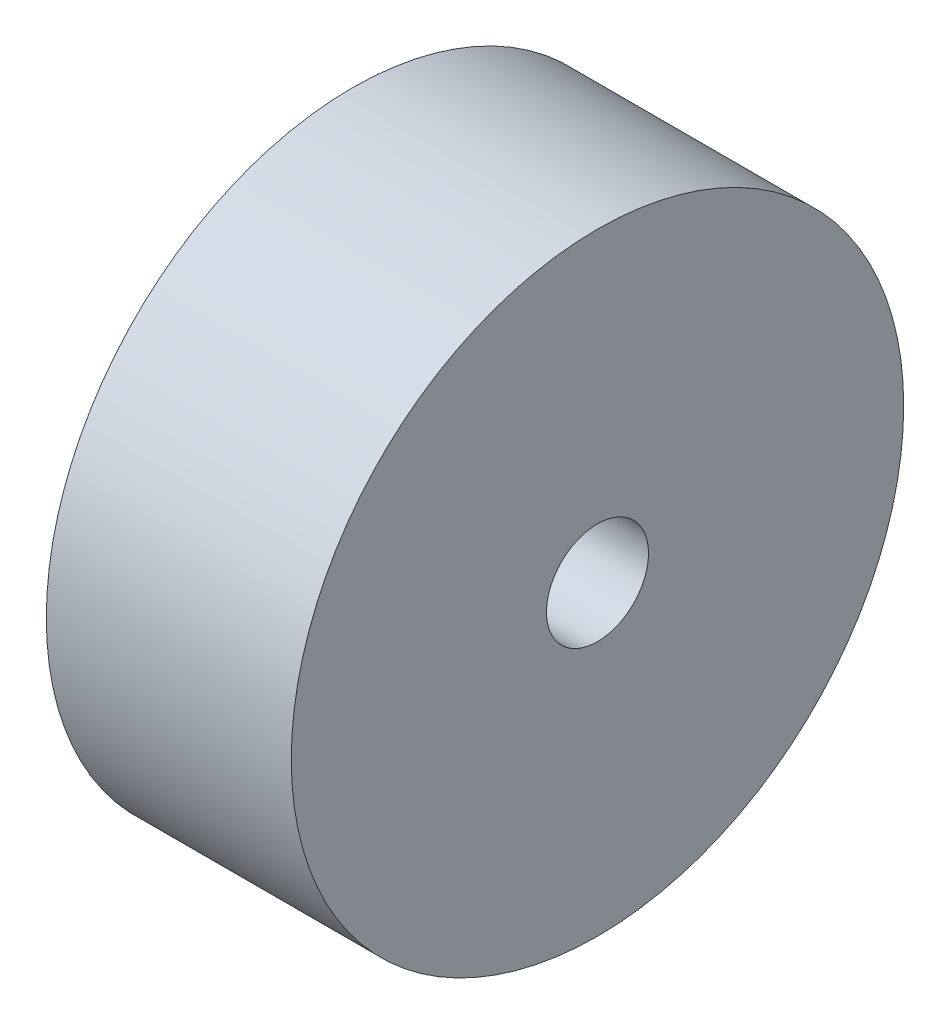
SolidWorks part; units mm, degrees
ref_plane "Front Plane" through (0, 0, 0) normal (0, 0, 1) x (1, 0, 0)
ref_plane "Top Plane" through (0, 0, 0) normal (0, 1, 0) x (1, 0, 0)
ref_plane "Right Plane" through (0, 0, 0) normal (1, 0, 0) x (0, 0, -1)
sketch "Sketch1" plane through (0, 0, 0) normal (1, 0, 0) x (0, 0, -1)
  circle A0 centre (0, 0) radius 75
  circle A1 centre (0, 0) radius 12.5
  dimension "D1" = 25
  dimension "D2" = 150
extrude "Boss-Extrude1" add sketch "Sketch1" along normal mid plane 60
